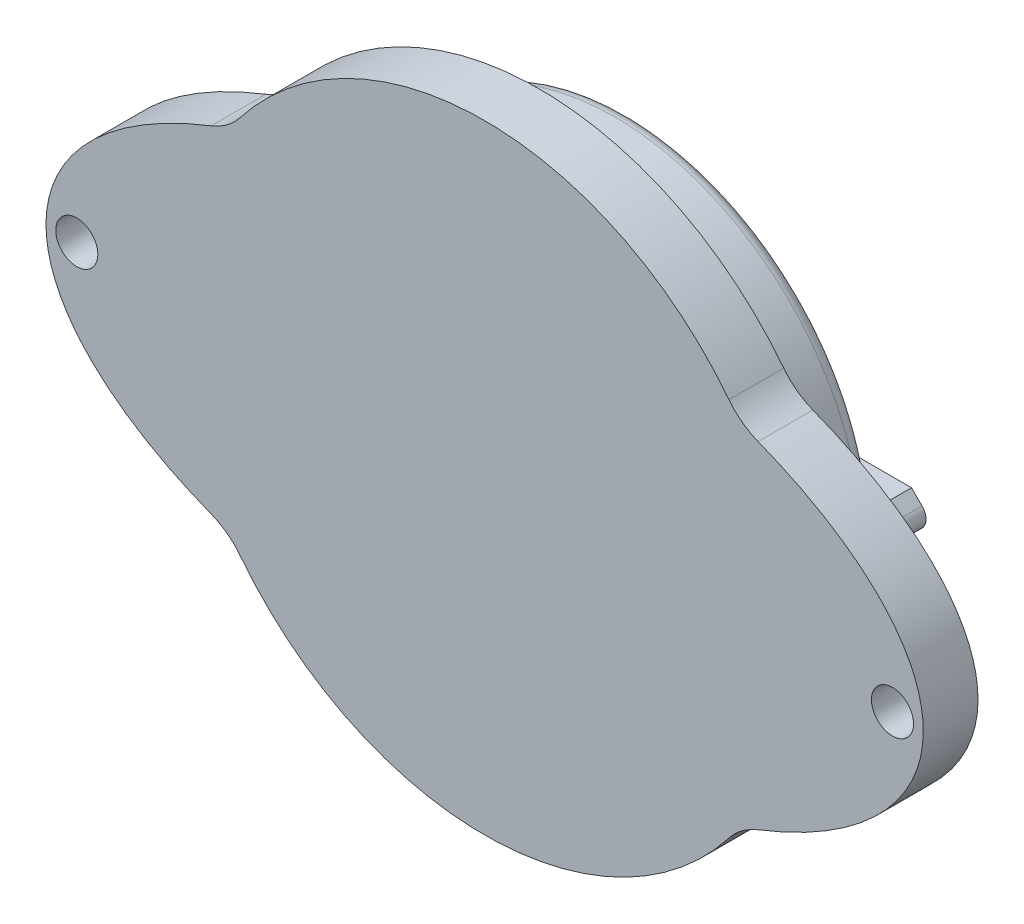
SolidWorks part; units mm, degrees
ref_plane "Front Plane" through (0, 0, 0) normal (0, 0, 1) x (1, 0, 0)
ref_plane "Top Plane" through (0, 0, 0) normal (0, 1, 0) x (1, 0, 0)
ref_plane "Right Plane" through (0, 0, 0) normal (1, 0, 0) x (0, 0, -1)
sketch "Sketch1" plane through (0, 0, 0) normal (0, 0, 1) x (1, 0, 0)
  arc A0 (-17.8586, -13.8749) -> (17.8586, -13.8749) centre (0, 0) ccw
  arc A2 (17.8586, 13.8749) -> (-17.8586, 13.8749) centre (0, 0) ccw
  arc A3 (19.9872, 12.2855) -> (17.8586, 13.8749) centre (21.807, 16.9425) cw
  arc A4 (19.9872, -12.2855) -> (17.8586, -13.8749) centre (21.807, -16.9425) ccw
  arc A5 (-17.8586, -13.8749) -> (-19.9872, -12.2855) centre (-21.807, -16.9425) ccw
  arc A6 (-17.8586, 13.8749) -> (-19.9872, 12.2855) centre (-21.807, 16.9425) cw
  circle A7 centre (-29.8092, 0) radius 1.5379
  circle A8 centre (29.8092, 0.0982) radius 1.5379
  ellipse E0 centre (0, 0) end of major axis (32.0608, 0) minor radius 15.7125 (-19.9872, 12.2855) -> (-19.9872, -12.2855) ccw
  ellipse E1 centre (0, 0) end of major axis (32.0608, 0) minor radius 15.7125 (19.9872, -12.2855) -> (19.9872, 12.2855) ccw
  dimension "D1" = 5
extrude "Boss-Extrude1" add sketch "Sketch1" along normal blind 4
sketch "Sketch2" plane through (0, 0, 0) normal (0, 0, -1) x (-1, 0, 0)
  circle A0 centre (0, 0) radius 20.698
  circle A1 centre (0, 0) radius 20.1
  dimension "D1" = 41.396
  dimension "D2" = 40.2
extrude "Cut-Extrude1" cut sketch "Sketch2" against normal blind 1
sketch "Sketch3" plane through (0, 0, 0) normal (0, 0, -1) x (-1, 0, 0)
  circle A0 centre (0, 0) radius 12.925
extrude "Boss-Extrude2" add sketch "Sketch3" along normal blind 0.5
sketch "Sketch4" plane through (0, 0, -0.5) normal (0, 0, -1) x (-1, 0, 0)
  circle A0 centre (0, 0) radius 18.1035
extrude "Boss-Extrude3" add sketch "Sketch4" along normal blind 6
fillet "Fillet1" radius 1 1 edges at (-18.1035, 0, -6.5)
sketch "Sketch5" plane through (0, 0, -6.5) normal (0, 0, -1) x (-1, 0, 0)
  line L0 (-17.7023, 0) -> (17.6369, 0) construction
  line L1 (-17.7023, 1.4725) -> (17.6369, 1.4725)
  line L2 (-17.7023, -1.4725) -> (17.6369, -1.4725)
  line L3 (17.6369, 1.4725) -> (18.4022, 0.7071)
  line L4 (18.4022, -0.7071) -> (17.6369, -1.4725)
  line L5 (-17.7023, 1.4725) -> (-18.4677, 0.7071)
  line L6 (-18.4677, -0.7071) -> (-17.7023, -1.4725)
  arc A0 (4.0257, 1.4725) -> (-4.0257, 1.4725) centre (0, 0) ccw
  arc A3 (-18.4677, 0.7071) -> (-18.4677, -0.7071) centre (-17.7606, 0) ccw
  arc A4 (18.4022, -0.7071) -> (18.4022, 0.7071) centre (17.6951, 0) ccw
  arc A5 (-4.0257, -1.4725) -> (4.0257, -1.4725) centre (0, 0) ccw
  point P5 (-0.0327, 0)
  dimension "D1" = 1
extrude "Boss-Extrude4" add sketch "Sketch5" along normal blind 3
scale "Scale1" scale about centroid uniform scaling yes scale factor 1
scale "Scale2" bodies to scale 106 scale about origin uniform scaling yes scale factor 0.5
scale "Scale3" scale about origin uniform scaling yes scale factor 0.5
